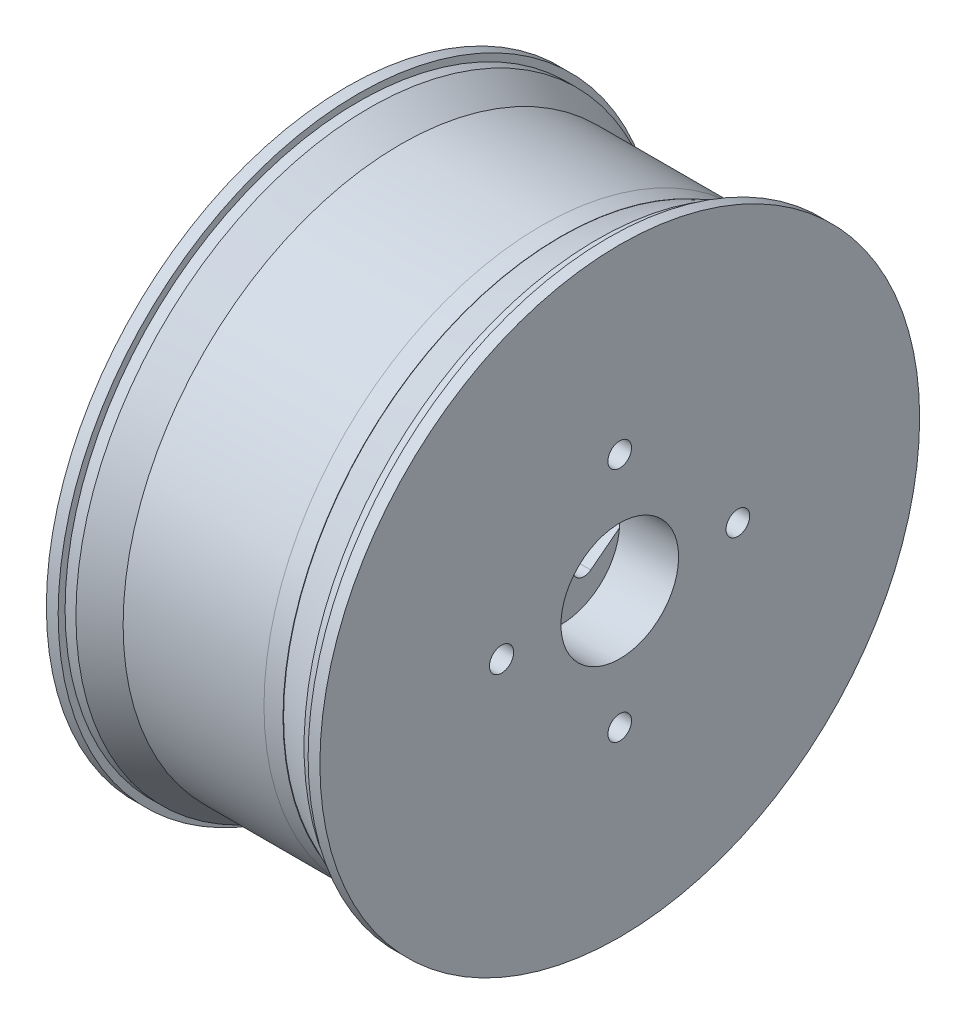
SolidWorks part; units mm, degrees
material "0.6010 (EN-GJL-100)"
ref_plane "Alzado" through (0, 0, 0) normal (0, 0, 1) x (1, 0, 0)
ref_plane "Planta" through (0, 0, 0) normal (0, 1, 0) x (1, 0, 0)
ref_plane "Vista lateral" through (0, 0, 0) normal (1, 0, 0) x (0, 0, -1)
sketch "Croquis1" plane through (0, 0, 0) normal (0, 1, 0) x (1, 0, 0)
  line L0 (-84.4923, 126.907) -> (-84.4923, 121.907)
  line L1 (-1.9923, 0) -> (-1.9924, 127) construction
  line L2 (-1.9924, 127) -> (-84.4923, 126.907) construction
  line L3 (-84.4923, 121.907) -> (-77.1997, 118.2576)
  line L4 (-77.1997, 118.2576) -> (-61.5999, 112.544)
  line L5 (-84.4923, -0.093) -> (-54.839, -0.093) construction
  line L6 (80.5077, -0.093) -> (80.5076, 126.907) construction
  line L7 (80.5076, 126.907) -> (-1.9924, 127) construction
  line L8 (-84.4923, 126.907) -> (-79.4923, 126.9126)
  line L9 (-79.4923, 126.9126) -> (-79.4923, 123.9809)
  line L10 (-79.4923, 123.9809) -> (-74.9071, 123.9809)
  line L11 (-74.9071, 123.9809) -> (-61.5999, 117.3217)
  line L12 (-61.5999, 117.3217) -> (-1.9924, 117.3217)
  line L13 (-61.5999, 112.544) -> (-54.839, 112.544)
  line L14 (-54.839, 112.544) -> (-54.839, 24.9201)
  line L15 (75.5076, 126.9127) -> (75.5076, 123.981)
  line L16 (57.6152, 117.3218) -> (-1.9924, 117.3217)
  line L17 (70.9223, 123.981) -> (57.6152, 117.3218)
  line L18 (75.5076, 123.981) -> (70.9223, 123.981)
  line L19 (80.5076, 126.9071) -> (75.5076, 126.9127)
  line L20 (80.5076, 126.9071) -> (80.5076, 121.9071)
  line L21 (73.215, 118.2577) -> (57.6152, 112.5441)
  line L22 (80.5076, 121.9071) -> (73.215, 118.2577)
  line L23 (57.6152, 112.5441) -> (-36.5458, 112.5441)
  line L24 (-36.5458, 112.5441) -> (-36.5458, 24.9201)
  line L26 (-36.5458, -0.093) -> (80.5077, -0.093) construction
  line L27 (-54.839, 24.9201) -> (-36.5458, 24.9201)
  dimension "D1" = 127
  dimension "D2" = 165
  dimension "D3" = 82.5
  dimension "D4" = 82.5
  dimension "D5" = 127
  dimension "D6" = 127
other "Alinear grupo1"
revolve "Revolución1" add sketch "Croquis1" angle 360 about L5
sketch "Croquis2" plane through (-54.839, 0, 0) normal (-1, 0, 0) x (0, 0, 1)
  line L0 (0, 0) -> (154.8769, 0) construction
  line L1 (0, 0) -> (134.1273, -77.4385) construction
  line L2 (0, 0) -> (77.4385, -134.1273) construction
  line L3 (0, 0) -> (0, -154.8769) construction
  line L4 (0, 0) -> (-77.4385, -134.1273) construction
  line L5 (0, 0) -> (-134.1273, -77.4385) construction
  line L6 (0, 0) -> (-154.8769, 0) construction
  line L7 (0, 0) -> (-134.1273, 77.4385) construction
  line L8 (0, 0) -> (-77.4385, 134.1273) construction
  line L9 (0, 0) -> (0, 154.8769) construction
  line L10 (0, 0) -> (77.4385, 134.1273) construction
  line L11 (0, 0) -> (50, 28.8675) construction
  line L12 (0, 0) -> (50, 0) construction
  line L13 (24.6647, -52.4265) -> (34.5164, -69.4902)
  line L14 (42.462, -69.9482) -> (53.7427, -55.311)
  line L15 (52.4265, 24.6647) -> (69.4902, 34.5164)
  line L16 (50.5384, -47.7377) -> (29.4059, -45.3112)
  line L17 (-52.4265, -24.6647) -> (-69.4902, -34.5164)
  line L18 (69.9482, 42.462) -> (55.311, 53.7427)
  line L19 (-69.9482, -42.462) -> (-55.311, -53.7427)
  line L21 (47.7377, 50.5384) -> (45.3112, 29.4059)
  line L22 (67.0637, 38.7192) -> (134.1273, 77.4385) construction
  line L23 (-47.7377, -50.5384) -> (-45.3112, -29.4059)
  line L24 (-24.6647, 52.4265) -> (-34.5164, 69.4902)
  line L25 (-42.462, 69.9482) -> (-53.7427, 55.311)
  line L26 (-50.5384, 47.7377) -> (-29.4059, 45.3112)
  line L27 (-98.4165, 0) -> (-96.5093, 16.6104) construction
  line L28 (-102.7485, 0.4974) -> (-100.8412, 17.1078)
  line L29 (-94.0846, -0.4974) -> (-92.1773, 16.113)
  line L30 (0, 98.4165) -> (16.6104, 96.5093) construction
  line L31 (0.4974, 102.7485) -> (17.1078, 100.8412)
  line L32 (-0.4974, 94.0846) -> (16.113, 92.1773)
  line L33 (98.4165, 0) -> (96.5093, -16.6104) construction
  line L34 (102.7485, -0.4974) -> (100.8412, -17.1078)
  line L35 (94.0846, 0.4974) -> (92.1773, -16.113)
  line L36 (0, -98.4165) -> (-16.6104, -96.5093) construction
  line L37 (-0.4974, -102.7485) -> (-17.1078, -100.8412)
  line L38 (0.4974, -94.0846) -> (-16.113, -92.1773)
  circle A0 centre (50, 0) radius 5
  circle A1 centre (0, -50) radius 5
  circle A2 centre (-50, 0) radius 5
  circle A3 centre (0, 50) radius 5
  arc A4 (45.4401, 30.5286) -> (52.4265, 24.6647) centre (50, 28.8675) ccw
  arc A5 (69.4902, 34.5164) -> (69.0722, 43.1371) centre (67.0637, 38.7192) ccw
  arc A6 (71.1559, 41.0819) -> (69.9482, 42.462) centre (67.0637, 38.7192) ccw
  arc A7 (55.311, 53.7427) -> (47.7112, 50.3079) centre (52.4265, 50) ccw
  arc A8 (53.7427, -55.311) -> (50.3079, -47.7112) centre (50, -52.4265) ccw
  arc A9 (45.3112, 29.4059) -> (45.9127, 26.5077) centre (50, 28.8675) ccw
  arc A10 (30.5286, -45.4401) -> (24.6647, -52.4265) centre (28.8675, -50) ccw
  arc A11 (34.5164, -69.4902) -> (43.1371, -69.0722) centre (38.7192, -67.0637) ccw
  arc A12 (-55.311, -53.7427) -> (-47.7112, -50.3079) centre (-52.4265, -50) ccw
  arc A13 (-45.4401, -30.5286) -> (-52.4265, -24.6647) centre (-50, -28.8675) ccw
  arc A14 (-69.4902, -34.5164) -> (-69.0722, -43.1371) centre (-67.0637, -38.7192) ccw
  arc A15 (-53.7427, 55.311) -> (-50.3079, 47.7112) centre (-50, 52.4265) ccw
  arc A16 (-30.5286, 45.4401) -> (-24.6647, 52.4265) centre (-28.8675, 50) ccw
  arc A17 (-34.5164, 69.4902) -> (-43.1371, 69.0722) centre (-38.7192, 67.0637) ccw
  arc A18 (-102.7485, 0.4974) -> (-94.0846, -0.4974) centre (-98.4165, 0) ccw
  arc A19 (-92.1773, 16.113) -> (-100.8412, 17.1078) centre (-96.5093, 16.6104) ccw
  arc A20 (0.4974, 102.7485) -> (-0.4974, 94.0846) centre (0, 98.4165) ccw
  arc A21 (16.113, 92.1773) -> (17.1078, 100.8412) centre (16.6104, 96.5093) ccw
  arc A22 (102.7485, -0.4974) -> (94.0846, 0.4974) centre (98.4165, 0) ccw
  arc A23 (92.1773, -16.113) -> (100.8412, -17.1078) centre (96.5093, -16.6104) ccw
  arc A24 (-0.4974, -102.7485) -> (0.4974, -94.0846) centre (0, -98.4165) ccw
  arc A25 (-16.113, -92.1773) -> (-17.1078, -100.8412) centre (-16.6104, -96.5093) ccw
  point P15 (0, 0)
  point P18 (58.5318, 33.7934)
  point P25 (0, 0)
  point P30 (59.7451, 44.3596)
  point P37 (51.2132, 39.4338)
  point P39 (-97.4629, 8.3052)
  point P79 (0, 0)
  point P89 (8.3052, 97.4629)
  point P96 (97.4629, -8.3052)
  point P103 (-8.3052, -97.4629)
  point P108 (0, 0)
  dimension "D2" = 4
  dimension "D1" = 12
  dimension "D3" = 4
  dimension "D4" = 4
extrude "Cortar-Extruir1" cut sketch "Croquis2" against normal through all
scale "Escala1" scale about centroid uniform scaling yes scale factor 0.8
sketch "Croquis3" plane through (0, 0, 0) normal (0, 1, 0) x (1, 0, 0)
  line L1 (0, 105.9698) -> (69.8788, 105.9698)
  line L2 (0, 105.9698) -> (0, -118.6356)
  line L3 (0, -118.6356) -> (69.8788, -118.6356)
  line L4 (69.8788, 105.9698) -> (69.8788, -118.6356)
extrude "Cortar-Extruir2" cut sketch "Croquis3" against normal blind 175 and the other way blind 255
sketch "Croquis4" plane through (0, 0, 0) normal (0, 1, 0) x (1, 0, 0)
  line L0 (-64.7724, 99.1652) -> (17.0848, 99.1652) construction
  line L1 (-64.7724, -99.353) -> (-64.7724, 99.1652) construction
  line L2 (-68.4406, 101.5106) -> (27.0006, 101.5106) construction
  line L3 (0, 93.8379) -> (12.2647, 99.1652)
  line L4 (12.2647, 99.1652) -> (15.9831, 99.1652)
  line L5 (15.9831, 99.1652) -> (15.9831, 101.5106)
  line L6 (15.9831, 101.5106) -> (21.7673, 101.5106)
  line L7 (21.7673, 101.5106) -> (21.7673, 0)
  line L8 (-30.2837, 93.8379) -> (-30.2837, -23.4091) construction
  line L9 (-6.4406, 93.8379) -> (-54.1267, 93.8379) construction
  line L10 (21.7673, 0) -> (0, 0)
  line L11 (0, 0) -> (0, 93.8379)
revolve "Revolución3" add sketch "Croquis4" angle 360 about L10
sketch "Croquis5" plane through (21.7673, 0, 0) normal (1, 0, 0) x (0, 0, -1)
  circle A0 centre (0, 0) radius 101.5106
extrude "Cortar-Extruir3" cut sketch "Croquis5" against normal blind 1.8
sketch "Croquis6" plane through (-48.718, 0, 0) normal (-1, 0, 0) x (0, 0, 1)
  circle A0 centre (0, 0) radius 19.9166
extrude "Cortar-Extruir4" cut sketch "Croquis6" against normal blind 123
sketch "Croquis7" plane through (-48.718, 0, 0) normal (-1, 0, 0) x (0, 0, 1)
  circle A0 centre (0.0195, 40) radius 4
  circle A1 centre (40.0195, 0) radius 4.0947
  circle A2 centre (-39.9805, 0) radius 4
  circle A3 centre (0.0195, -40) radius 4
extrude "Cortar-Extruir5" cut sketch "Croquis7" against normal blind 123
